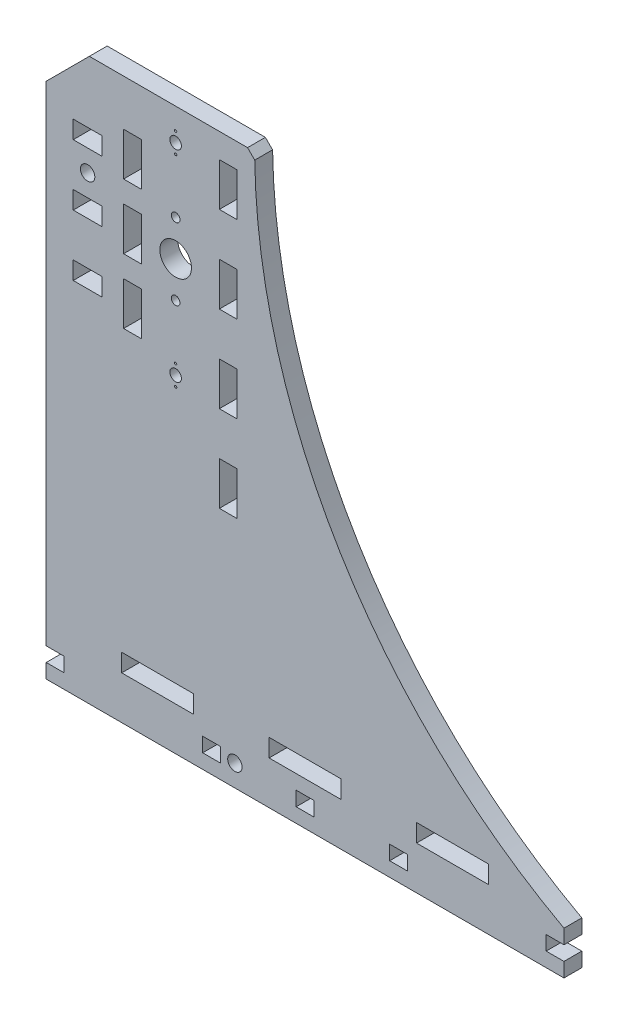
SolidWorks part; units mm, degrees
ref_plane "Front" through (0, 0, 0) normal (0, 0, 1) x (1, 0, 0)
ref_plane "Top" through (0, 0, 0) normal (0, 1, 0) x (1, 0, 0)
ref_plane "Right" through (0, 0, 0) normal (1, 0, 0) x (0, 0, -1)
sketch "Sketch1" plane through (0, 0, 0) normal (0, 0, 1) x (1, 0, 0)
  line L0 (-90, 390) -> (-90, 0) construction
  line L1 (-180, 0) -> (180, 0)
  line L2 (-180, 0) -> (-180, 10)
  line L3 (71.2, 10) -> (71.2, 20)
  line L4 (180, 0) -> (180, 10)
  line L5 (-6.2, 10) -> (6.2, 10)
  line L6 (-6.2, 10) -> (-6.2, 20)
  line L7 (-40, 390) -> (-140, 390)
  line L8 (-6.2, 20) -> (6.2, 20)
  line L9 (0, 0) -> (0, 52.5688) construction
  line L10 (-180, 10) -> (-167.6, 10)
  line L11 (180, 20) -> (180, 30)
  line L12 (-180, 20) -> (-167.6, 20)
  line L13 (-167.6, 10) -> (-167.6, 20)
  line L14 (180, 10) -> (167.6, 10)
  line L15 (167.6, 10) -> (167.6, 20)
  line L16 (180, 20) -> (167.6, 20)
  line L17 (-180, 20) -> (-180, 30)
  line L18 (-180, 5) -> (0, 5) construction
  line L19 (-90, 298) -> (-24.3227, 298) construction
  line L20 (-180, 30) -> (-180, 360)
  line L21 (6.2, 10) -> (6.2, 20)
  line L22 (-6.2, 10) -> (6.2, 20) construction
  line L23 (-6.2, 20) -> (6.2, 10) construction
  line L24 (58.8, 20) -> (71.2, 20)
  line L25 (58.8, 10) -> (58.8, 20)
  line L26 (58.8, 10) -> (71.2, 10)
  line L27 (-71.2, 20) -> (-58.8, 20)
  line L28 (-58.8, 10) -> (-58.8, 20)
  line L29 (-71.2, 10) -> (-58.8, 10)
  line L30 (-71.2, 10) -> (-71.2, 20)
  line L31 (58.8, 10) -> (6.2, 10) construction
  line L32 (-6.2, 10) -> (-58.8, 10) construction
  line L33 (127.5, 42.4) -> (127.5, 30)
  line L34 (-25, 42.4) -> (25, 42.4)
  line L35 (-25, 42.4) -> (-25, 30)
  line L36 (-25, 30) -> (25, 30)
  line L37 (25, 42.4) -> (25, 30)
  line L38 (-25, 42.4) -> (25, 30) construction
  line L39 (-25, 30) -> (25, 42.4) construction
  line L40 (77.5, 42.4) -> (127.5, 42.4)
  line L41 (77.5, 30) -> (127.5, 30)
  line L42 (77.5, 42.4) -> (77.5, 30)
  line L43 (-127.5, 42.4) -> (-77.5, 42.4)
  line L44 (-127.5, 42.4) -> (-127.5, 30)
  line L45 (-127.5, 30) -> (-77.5, 30)
  line L46 (-77.5, 42.4) -> (-77.5, 30)
  line L47 (-25.0003, 29.8097) -> (-77.5, 30) construction
  line L48 (25, 30) -> (77.5, 30) construction
  line L49 (-25, 30) -> (-25.0003, 29.8097) construction
  line L50 (-127.5, 30) -> (-180, 30) construction
  line L51 (127.5, 30) -> (180, 30) construction
  line L52 (-120, 390) -> (-120, 258.0959) construction
  line L53 (-140, 390) -> (-150, 390)
  line L54 (-126.2, 313) -> (-113.8, 313)
  line L55 (-126.2, 313) -> (-126.2, 283)
  line L56 (-126.2, 283) -> (-113.8, 283)
  line L57 (-113.8, 313) -> (-113.8, 283)
  line L58 (-126.2, 313) -> (-113.8, 283) construction
  line L59 (-126.2, 283) -> (-113.8, 313) construction
  line L60 (-113.8, 358) -> (-113.8, 328)
  line L61 (-126.2, 358) -> (-113.8, 358)
  line L62 (-126.2, 358) -> (-126.2, 328)
  line L63 (-126.2, 328) -> (-113.8, 328)
  line L64 (-113.8, 268) -> (-113.8, 238)
  line L65 (-126.2, 268) -> (-113.8, 268)
  line L66 (-126.2, 268) -> (-126.2, 238)
  line L67 (-126.2, 238) -> (-113.8, 238)
  line L68 (-161.2, 346.6) -> (-141.2, 346.6)
  line L69 (-161.2, 304.2) -> (-141.2, 304.2)
  line L70 (-161.2, 304.2) -> (-161.2, 291.8)
  line L71 (-161.2, 291.8) -> (-141.2, 291.8)
  line L72 (-141.2, 304.2) -> (-141.2, 291.8)
  line L73 (-161.2, 304.2) -> (-141.2, 291.8) construction
  line L74 (-161.2, 291.8) -> (-141.2, 304.2) construction
  line L75 (-141.2, 346.6) -> (-141.2, 334.2)
  line L76 (-161.2, 334.2) -> (-141.2, 334.2)
  line L77 (-161.2, 346.6) -> (-161.2, 334.2)
  line L78 (-161.2, 249.4) -> (-141.2, 249.4)
  line L79 (-141.2, 261.8) -> (-141.2, 249.4)
  line L80 (-161.2, 261.8) -> (-141.2, 261.8)
  line L81 (-161.2, 261.8) -> (-161.2, 249.4)
  line L82 (-151.2, 298) -> (-151.2, 319.2) construction
  line L83 (-180, 360) -> (-150, 390)
  line L84 (-59.6, 0) -> (-59.6, 390) construction
  line L85 (-47.2, 373) -> (-59.6, 373)
  line L86 (-47.2, 283) -> (-59.6, 283)
  line L87 (-47.2, 283) -> (-47.2, 313)
  line L88 (-47.2, 313) -> (-59.6, 313)
  line L89 (-59.6, 283) -> (-59.6, 313)
  line L90 (-47.2, 343) -> (-47.2, 373)
  line L91 (-47.2, 343) -> (-59.6, 343)
  line L92 (-59.6, 343) -> (-59.6, 373)
  line L93 (-47.2, 223) -> (-59.6, 223)
  line L94 (-59.6, 223) -> (-59.6, 253)
  line L95 (-47.2, 223) -> (-47.2, 253)
  line L96 (-47.2, 253) -> (-59.6, 253)
  line L97 (-47.2, 163) -> (-59.6, 163)
  line L98 (-59.6, 163) -> (-59.6, 193)
  line L99 (-47.2, 163) -> (-47.2, 193)
  line L100 (-47.2, 193) -> (-59.6, 193)
  line L101 (-35.0006, 385.0006) -> (-40, 390)
  arc A0 (-35.0006, 385.0006) -> (180, 30) centre (375.9542, 391.2828) ccw
  circle A3 centre (-151.2, 319.2) radius 5
  circle A7 centre (-90, 298) radius 11
  circle A8 centre (-90, 323) radius 3
  circle A9 centre (-90, 368) radius 4
  circle A10 centre (-90, 375) radius 0.8
  circle A11 centre (-90, 361) radius 0.8
  circle A12 centre (-90, 221) radius 0.8
  circle A13 centre (-90, 228) radius 4
  circle A14 centre (-90, 235) radius 0.8
  circle A15 centre (-90, 273) radius 3
  circle A16 centre (-48.8, 15) radius 5
  point P4 (0, 15)
  point P24 (-90, 5)
  point P32 (0, 36.2)
  point P57 (-120, 298)
  point P66 (-151.2, 298)
  dimension "D21" = 22
  dimension "D22" = 6
  dimension "D25" = 8
  dimension "D26" = 1.6
  dimension "D30" = 10
  dimension "D42" = 10
  dimension "D2" = 360
  dimension "D3" = 10
  dimension "D4" = 12.4
  dimension "D1" = 4.9994
  dimension "D7" = 100
  dimension "D8" = 30
  dimension "D11" = 52.6
  dimension "D12" = 50
  dimension "D13" = 12.4
  dimension "D16" = 30
  dimension "D5" = 390
  dimension "D23" = 25
  dimension "D24" = 70
  dimension "D27" = 7
  dimension "D28" = 7
  dimension "D29" = 92
  dimension "D17" = 5
  dimension "D18" = 12.4
  dimension "D19" = 30
  dimension "D20" = 30
  dimension "D32" = 15
  dimension "D34" = 15
  dimension "D35" = 20
  dimension "D36" = 12.4
  dimension "D37" = 15
  dimension "D39" = 30
  dimension "D41" = 30
  dimension "D43" = 15
  dimension "D44" = 30
  dimension "D45" = 30
  dimension "D46" = 30.4
  dimension "D47" = 12.4
  dimension "D48" = 30
  dimension "D51" = 30
  dimension "D52" = 30
  dimension "D6" = 135
  dimension "D9" = 2
  dimension "D10" = 2
  dimension "D14" = 2
  dimension "D15" = 2
  dimension "D31" = 2
  dimension "D33" = 2
  dimension "D38" = 2
  dimension "D40" = 2
  dimension "D49" = 2
  dimension "D50" = 3
extrude "Boss-Extrude1" add sketch "Sketch1" along normal blind 12.4
equation "\"material-thickness\"= 12.4mm"
equation "\"sideplate-height\"= 390mm"
equation "\"baseplate-height\"= 360mm"
equation "\"tab-width-small\"= 20mm ' Width of the small version of the Tab"
equation "\"tab-width-large\"= 30mm ' Width of the large version of the Tab"
equation "\"spindle-thread-rbearing-diameter\"= 22mm ' Outer diameter of the rotational bearing"
equation "\"spindle-thread-height\"= 30.4mm ' Height from the base to the spindle for the stepper motor / Servo"
equation "\"linear-bar-dia\"= 8mm ' Diameter of the metal slide bar used on the X Axis"
equation "\"D2@Sketch1\"=\"baseplate-height\""
equation "\"D1@Boss-Extrude1\"=\"material-thickness\""
equation "\"D4@Sketch1\"=\"material-thickness\""
equation "\"D5@Sketch1\"=\"sideplate-height\""
equation "\"D13@Sketch1\"=\"material-thickness\""
equation "\"D21@Sketch1\"=\"spindle-thread-rbearing-diameter\""
equation "\"D25@Sketch1\"=\"linear-bar-dia\""
equation "\"D18@Sketch1\"=\"material-thickness\""
equation "\"D19@Sketch1\"=\"tab-width-large\""
equation "\"D35@Sketch1\"=\"tab-width-small\""
equation "\"D36@Sketch1\"=\"material-thickness\""
equation "\"D46@Sketch1\"=\"spindle-thread-height\""
equation "\"D47@Sketch1\"=\"material-thickness\""
equation "\"D48@Sketch1\"=\"tab-width-large\""
